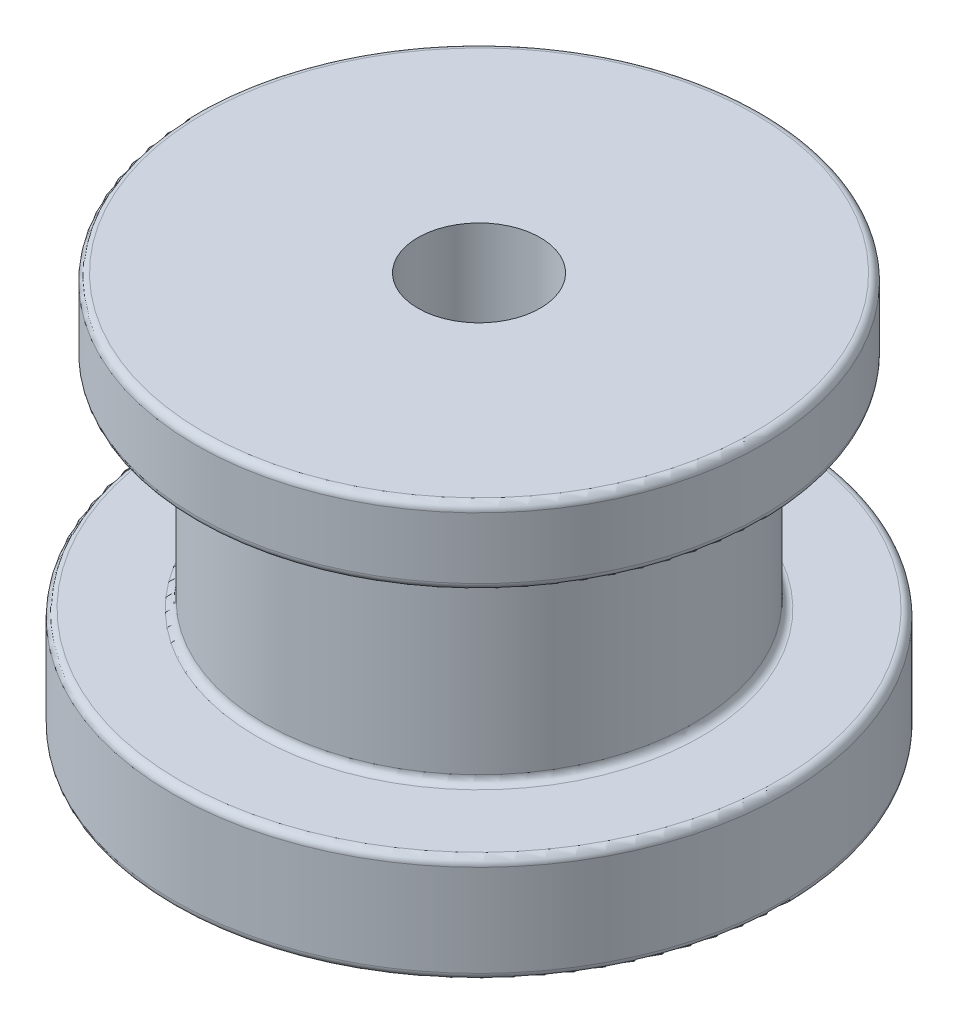
SolidWorks part; units mm, degrees
ref_plane "Front Plane" through (0, 0, 0) normal (0, 0, 1) x (1, 0, 0)
ref_plane "Top Plane" through (0, 0, 0) normal (0, 1, 0) x (1, 0, 0)
ref_plane "Right Plane" through (0, 0, 0) normal (1, 0, 0) x (0, 0, -1)
sketch "Sketch2" plane through (0, 0, 0) normal (1, 0, 0) x (0, 0, -1)
  line L0 (0, 13) -> (0, -13) construction
  line L1 (4, -13) -> (19.5, -13)
  line L2 (20, -12.5) -> (20, -6.5)
  line L3 (19.5, -6) -> (14.5, -6)
  line L4 (14, -5.5) -> (14, 7.5)
  line L5 (14.5, 8) -> (18, 8)
  line L6 (18.5, 8.5) -> (18.5, 12.5)
  line L7 (18, 13) -> (4, 13)
  line L8 (4, 13) -> (4, -13)
  arc A0 (19.5, -13) -> (20, -12.5) centre (19.5, -12.5) ccw
  arc A1 (20, -6.5) -> (19.5, -6) centre (19.5, -6.5) ccw
  arc A2 (14.5, -6) -> (14, -5.5) centre (14.5, -5.5) cw
  arc A3 (14, 7.5) -> (14.5, 8) centre (14.5, 7.5) cw
  arc A4 (18, 8) -> (18.5, 8.5) centre (18, 8.5) ccw
  arc A5 (18.5, 12.5) -> (18, 13) centre (18, 12.5) ccw
  point P4 (0, 0)
  point P14 (20, -13)
  point P17 (20, -6)
  point P24 (18.5, 8)
  point P27 (18.5, 13)
  dimension "D8" = 0.5
  dimension "D1" = 26
  dimension "D2" = 8
  dimension "D3" = 40
  dimension "D4" = 28
  dimension "D5" = 37
  dimension "D6" = 7
  dimension "D7" = 5
revolve "Revolve1" add sketch "Sketch2" angle 360 about L0
